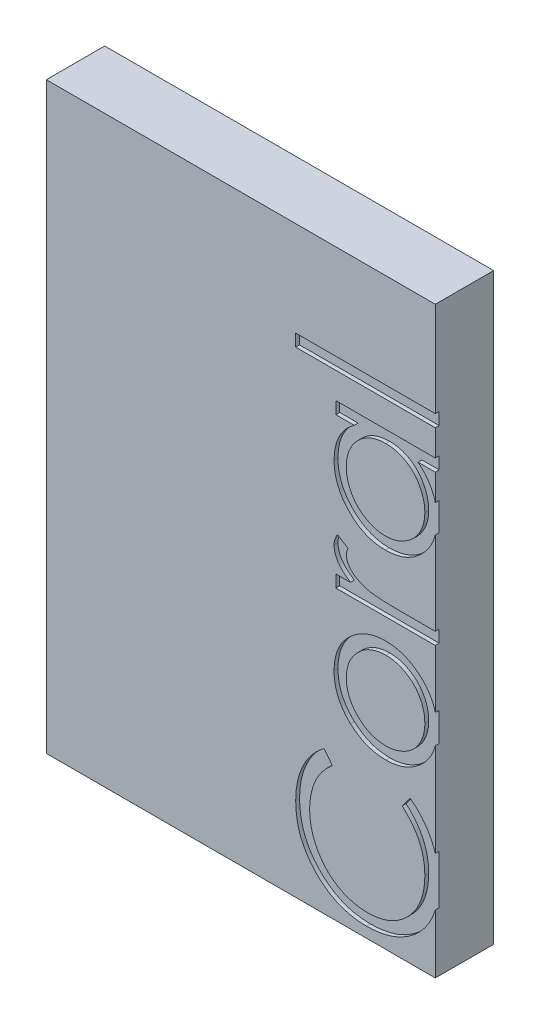
SolidWorks part; units mm, degrees
ref_plane "Front Plane" through (0, 0, 0) normal (0, 0, 1) x (1, 0, 0)
ref_plane "Top Plane" through (0, 0, 0) normal (0, 1, 0) x (1, 0, 0)
ref_plane "Right Plane" through (0, 0, 0) normal (1, 0, 0) x (0, 0, -1)
sketch "Sketch1" plane through (0, 0, 0) normal (0, 0, 1) x (1, 0, 0)
  line L1 (5, -7.5) -> (-5, -7.5)
  line L2 (5, -7.5) -> (5, 7.5)
  line L3 (5, 7.5) -> (-5, 7.5)
  line L4 (-5, -7.5) -> (-5, 7.5)
  line L5 (5, -7.5) -> (-5, 7.5) construction
  line L6 (5, 7.5) -> (-5, -7.5) construction
  point P0 (0, 0)
  dimension "D1" = 15
  dimension "D2" = 10
extrude "Boss-Extrude1" add sketch "Sketch1" along normal blind 1.5
sketch "Sketch2" plane through (0, 0, 1.5) normal (0, 0, 1) x (1, 0, 0)
  text T0 "Coral"
extrude "Cut-Extrude1" cut sketch "Sketch2" against normal blind 0.1
